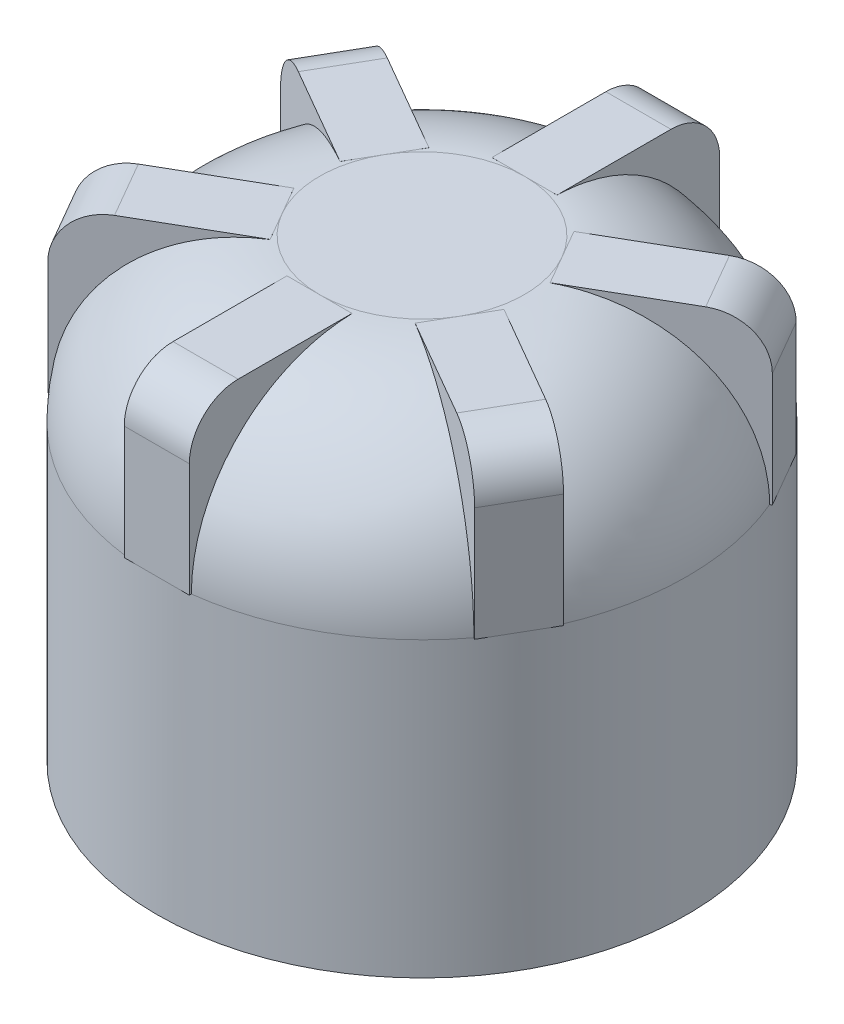
SolidWorks part; units mm, degrees
ref_plane "Front Plane" through (0, 0, 0) normal (0, 0, 1) x (1, 0, 0)
ref_plane "Top Plane" through (0, 0, 0) normal (0, 1, 0) x (1, 0, 0)
ref_plane "Right Plane" through (0, 0, 0) normal (1, 0, 0) x (0, 0, -1)
sketch "Sketch1" plane through (0, 0, 0) normal (0, 1, 0) x (1, 0, 0)
  circle A0 centre (0, 0) radius 16.3
  dimension "D1" = 32.6
extrude "Boss-Extrude1" add sketch "Sketch1" along normal blind 28
fillet "Fillet1" radius 10 1 edges at (0, 28, 16.3)
ref_plane "Plane1" through (0, 18, 0) normal (0, -1, 0) x (-1, 0, 0)
sketch "Sketch4" plane through (0, 0, 0) normal (0, -1, 0) x (1, 0, 0)
  circle A0 centre (0, 0) radius 5.2
  dimension "D1" = 10.4
ref_plane "Plane2" through (0, 7, 0) normal (0, -1, 0) x (-1, 0, 0)
sketch "Sketch5" plane through (0, 7, 0) normal (0, -1, 0) x (-1, 0, 0)
  circle A0 centre (0, 0) radius 3.05
  dimension "D1" = 6.1
loft "Cut-Loft1" cut profiles "Sketch4", "Sketch5"
sketch "Sketch6" plane through (0, 7, 0) normal (0, -1, 0) x (1, 0, 0)
  circle A0 centre (0, 0) radius 3.05
  dimension "D1" = 6.1
extrude "Cut-Extrude1" cut sketch "Sketch6" against normal blind 9
sketch "Sketch7" plane through (0, 16, 0) normal (0, -1, 0) x (1, 0, 0)
  line L2 (-2.4249, 1.85) -> (2.4249, 1.85)
  circle A3 centre (0, 0) radius 3.05 construction
  arc A4 (-2.4249, 1.85) -> (2.4249, 1.85) centre (0, 0) cw
  dimension "D2" = 3.05
  dimension "D1" = 4.9
extrude "Boss-Extrude3" add sketch "Sketch7" along normal blind 9
sketch "Sketch8" plane through (0, 18, 0) normal (0, -1, 0) x (-1, 0, 0)
  line L1 (0, 6.3) -> (-2, 6.3)
  line L2 (0, 6.3) -> (2, 6.3)
  line L3 (-2, 6.3) -> (-2, 16.3)
  line L4 (-2, 16.3) -> (0, 16.3)
  line L5 (0, 16.3) -> (2, 16.3)
  line L6 (2, 16.3) -> (2, 6.3)
  circle A0 centre (0, 0) radius 6.3 construction
  circle A1 centre (0, 0) radius 16.3 construction
  dimension "D1" = 2
  dimension "D2" = 2
  dimension "D3" = 2
  dimension "D4" = 10
extrude "Boss-Extrude4" add sketch "Sketch8" against normal blind 10
pattern_circular "CirPattern1" count 6 over 360 about axis through (0, 0, 0) along (0, 1, 0) of "Boss-Extrude4"
fillet "Fillet2" radius 3 6 edges at (-14.1162, 28, 8.15) (0, 28, 16.3) (-14.1162, 28, -8.15) (0, 28, -16.3) (14.1162, 28, -8.15) (14.1162, 28, 8.15)
